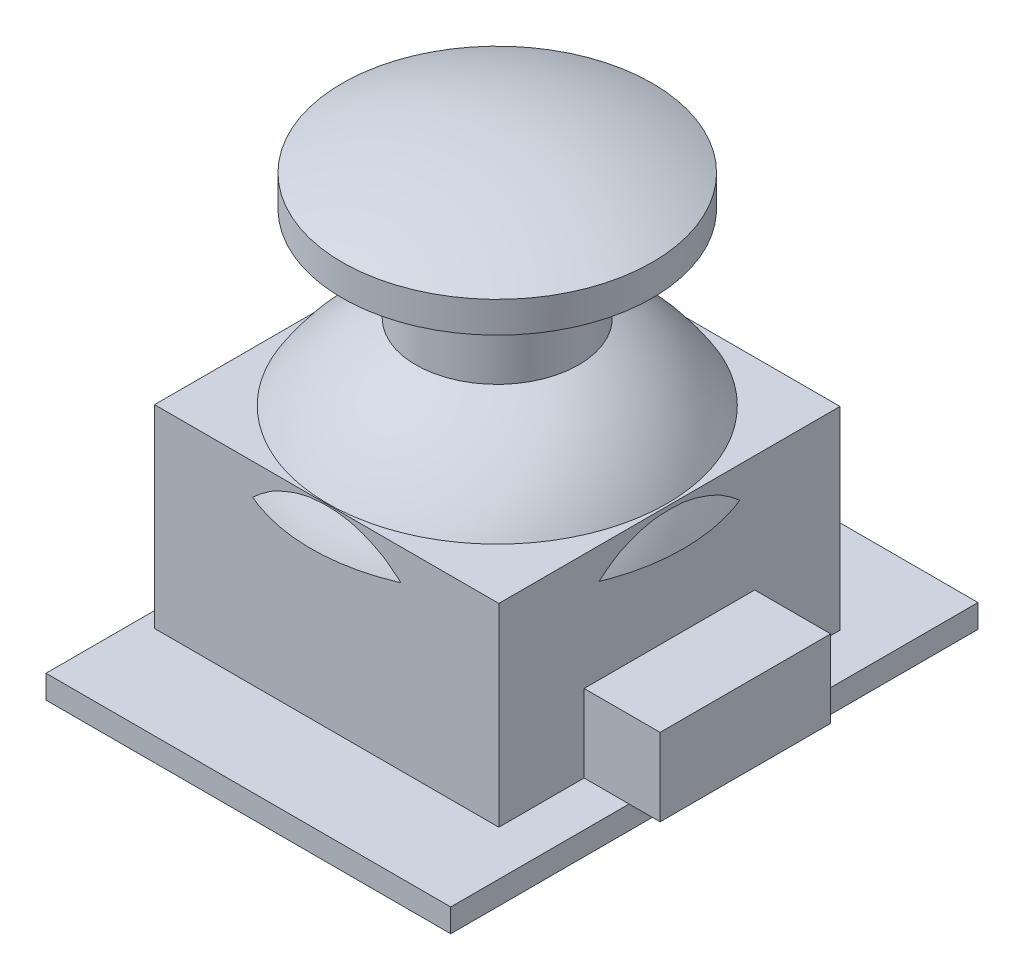
SolidWorks part; units mm, degrees
ref_plane "Front Plane" through (0, 0, 0) normal (0, 0, 1) x (1, 0, 0)
ref_plane "Top Plane" through (0, 0, 0) normal (0, 1, 0) x (1, 0, 0)
ref_plane "Right Plane" through (0, 0, 0) normal (1, 0, 0) x (0, 0, -1)
sketch "Sketch1" plane through (0, 0, 0) normal (0, 1, 0) x (1, 0, 0)
  line L1 (-13.05, 17) -> (13.05, 17)
  line L2 (-13.05, 17) -> (-13.05, -17)
  line L3 (-13.05, -17) -> (13.05, -17)
  line L4 (13.05, 17) -> (13.05, -17)
  line L5 (0, -17) -> (0, 17) construction
  line L6 (-13.05, 0) -> (13.05, 0) construction
  point P0 (0, 0)
  dimension "D1" = 34
  dimension "D2" = 26.1
extrude "Boss-Extrude1" add sketch "Sketch1" along normal blind 1.5
sketch "Sketch2" plane through (0, 1.5, 0) normal (0, 1, 0) x (1, 0, 0)
  line L1 (-12.05, 11) -> (10.15, 11)
  line L2 (-12.05, 11) -> (-12.05, -11)
  line L3 (-12.05, -11) -> (10.15, -11)
  line L4 (10.15, 11) -> (10.15, -11)
  line L10 (-12.05, -11) -> (10.15, 11) construction
  line L11 (-13.05, 17) -> (13.05, 17) construction
  line L12 (13.05, 17) -> (13.05, -17) construction
  line L13 (-13.05, 17) -> (-13.05, -17) construction
  line L14 (-13.05, 17) -> (-13.05, -17) construction
  point P0 (-0.95, 0)
  point P4 (-0.95, 0)
  dimension "D1" = 17
  dimension "D2" = 14
  dimension "D3" = 1
  dimension "D4" = 6
  dimension "D5" = 12.1
extrude "Boss-Extrude2" add sketch "Sketch2" along normal blind 12.5 separate body
sketch "Sketch3" plane through (0, 1.5, 0) normal (0, 1, 0) x (1, 0, 0)
  line L1 (10.15, 5.5) -> (15.05, 5.5)
  line L2 (10.15, 5.5) -> (10.15, -5.5)
  line L3 (10.15, -5.5) -> (15.05, -5.5)
  line L4 (15.05, 5.5) -> (15.05, -5.5)
  line L5 (10.15, 11) -> (10.15, -11) construction
  line L6 (13.05, -17) -> (13.05, 17) construction
  point P8 (10.15, 0)
  point P9 (10.15, 0)
  dimension "D1" = 11
  dimension "D2" = 2
extrude "Boss-Extrude3" add sketch "Sketch3" along normal blind 5
sketch "Sketch4" plane through (0, 14, 0) normal (0, 1, 0) x (1, 0, 0)
  circle A0 centre (0, 0) radius 2
  dimension "D1" = 4
extrude "Boss-Extrude4" add sketch "Sketch4" along normal blind 7.5
sketch "Sketch5" plane through (0, 21.5, 0) normal (0, 1, 0) x (1, 0, 0)
  line L0 (-13.05, 0) -> (13.05, 0) construction
  line L1 (1.5, 1.3229) -> (2, 1.3229)
  line L2 (1.5, 1.3229) -> (1.5, -1.3229)
  line L3 (1.5, -1.3229) -> (2, -1.3229)
  line L4 (2, 1.3229) -> (2, -1.3229)
  line L5 (0, -17) -> (0, 17) construction
  circle A1 centre (0, 0) radius 2 construction
  point P11 (2, 0)
  dimension "D1" = 1.5
extrude "Cut-Extrude1" cut sketch "Sketch5" against normal offset from surface (6.5 mm away) 1 up to face at (0, 14, 2)
mirror "Mirror1" about plane through (0, 0, 0) normal (1, 0, 0) of "Cut-Extrude1"
sketch "Sketch9" plane through (0, 0, 0) normal (0, 0, 1) x (1, 0, 0)
  line L0 (-0.95, 18.3441) -> (-0.95, 29.2)
  line L1 (-999.9174, 29.2) -> (49000.0826, 29.2) construction
  line L4 (-997.6311, 7) -> (49002.3689, 7) construction
  line L5 (14.355, 0) -> (-14.355, 0) construction
  line L6 (4.3, 25) -> (4.3, 18.8927)
  line L7 (4.3, 25) -> (9.05, 25)
  line L8 (9.05, 25) -> (9.05, 27)
  line L9 (-1021.7489, 12) -> (48978.2511, 12) construction
  line L10 (10.5064, 12) -> (11.05, 12)
  line L11 (4.3, 18.3441) -> (-0.95, 18.3441)
  line L13 (-0.95, -961.886) -> (-0.95, 49038.114) construction
  circle A0 centre (-0.95, 7) radius 13 construction
  arc A3 (4.3, 18.8927) -> (11.05, 12) centre (-0.95, 7) cw
  arc A4 (-0.95, 29.2) -> (9.05, 27) centre (-0.95, 5.3727) cw
  arc A5 (4.3, 18.3441) -> (10.5064, 12) centre (-0.95, 7) cw
  dimension "D1" = 26
  dimension "D9" = 0.5
  dimension "D2" = 7
  dimension "D3" = 5
  dimension "D4" = 5.25
  dimension "D5" = 2
  dimension "D6" = 13
  dimension "D7" = 17.2
  dimension "D8" = 10
revolve "Revolve1" add sketch "Sketch9" angle 360 about L13
